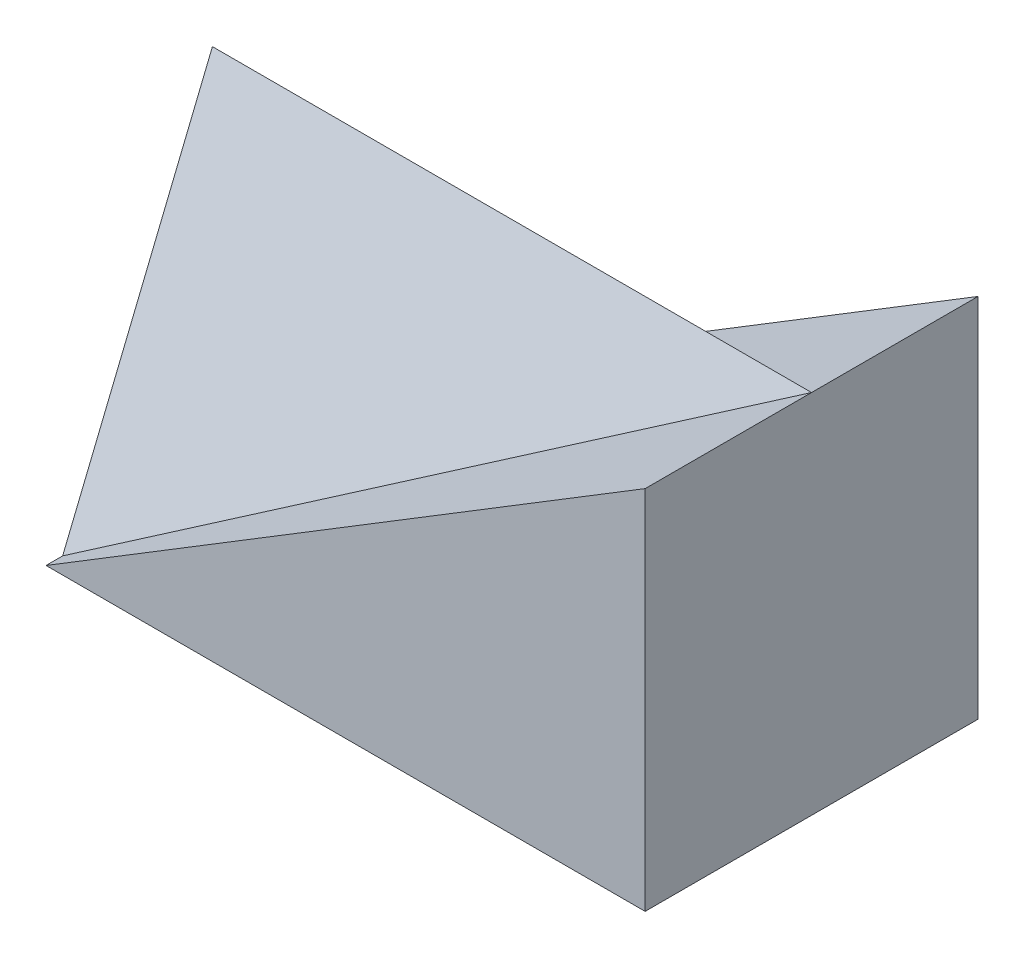
SolidWorks part; units mm, degrees
ref_plane "Front Plane" through (0, 0, 0) normal (0, 0, 1) x (1, 0, 0)
ref_plane "Top Plane" through (0, 0, 0) normal (0, 1, 0) x (1, 0, 0)
ref_plane "Right Plane" through (0, 0, 0) normal (1, 0, 0) x (0, 0, -1)
sketch "Sketch1" plane through (0, 0, 0) normal (0, 0, 1) x (1, 0, 0)
  line L0 (0, 0) -> (36000, 0)
  line L1 (36000, 0) -> (36000, 22000)
  line L2 (36000, 22000) -> (0, 0)
  dimension "D1" = 22000
  dimension "D2" = 36000
extrude "Boss-Extrude1" add sketch "Sketch1" along normal blind 20000
sketch "Sketch3" plane through (36000, 0, 0) normal (1, 0, 0) x (0, 0, -1)
  line L0 (-10000, 26305.5486) -> (-10000, -1503.5041) construction
  line L2 (-10000, 22000) -> (-19000, 0)
  line L4 (-20000, 22000) -> (0, 22000) construction
  line L5 (-20000, 0) -> (0, 0) construction
  line L6 (-19000, 0) -> (-1000, 0)
  line L7 (-1000, 0) -> (-10000, 22000)
  dimension "D1" = 1000
  dimension "D2" = 1000
extrude "Boss-Extrude3" add sketch "Sketch3" against normal blind 36000
